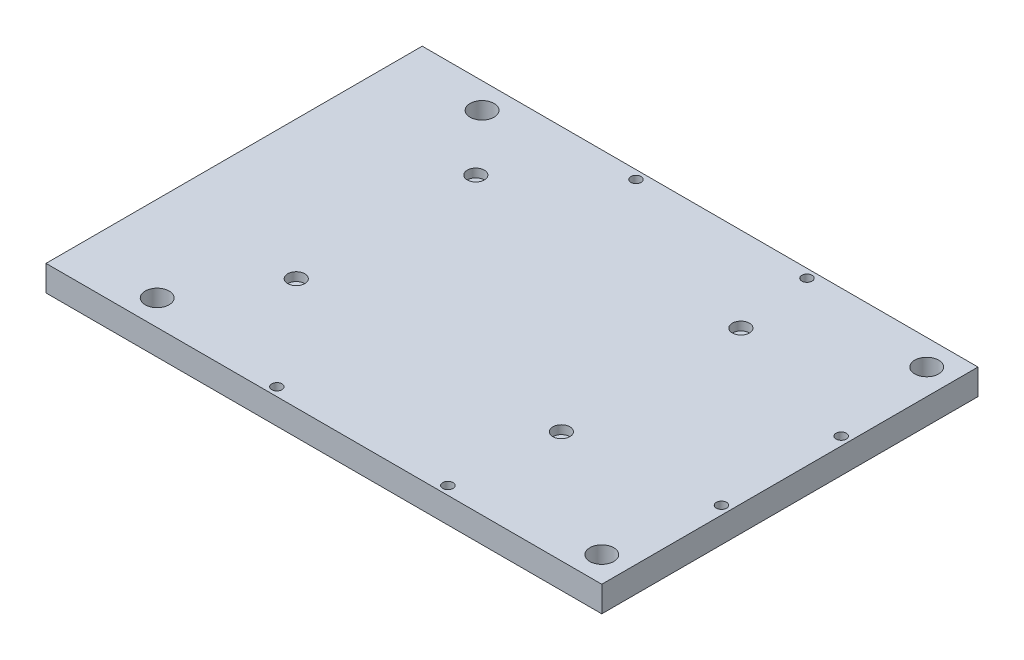
SolidWorks part; units mm, degrees
ref_plane "Front Plane" through (0, 0, 0) normal (0, 0, 1) x (1, 0, 0)
ref_plane "Top Plane" through (0, 0, 0) normal (0, 1, 0) x (1, 0, 0)
ref_plane "Right Plane" through (0, 0, 0) normal (1, 0, 0) x (0, 0, -1)
sketch "Sketch2" plane through (0, 0, 0) normal (0, 1, 0) x (1, 0, 0)
  line L0 (-154.9031, -110) -> (170.0969, -110)
  line L7 (-154.9031, 110) -> (-154.9031, -110)
  line L22 (170.0969, -110) -> (170.0969, 110)
  line L24 (70.8088, -52.5) -> (63.3088, -52.5)
  line L25 (70.8088, -60) -> (70.8088, -52.5)
  line L26 (170.0969, 0) -> (170.0969, 35)
  line L27 (70.8088, 60) -> (50.8088, 60)
  line L28 (-154.9031, 110) -> (170.0969, 110)
  line L29 (170.0969, 35) -> (165.0969, 35)
  line L30 (70.8088, -60) -> (70.8088, 60)
  line L31 (-99.1912, -60) -> (-99.1912, 0)
  line L32 (50.8088, -60) -> (-99.1912, -60)
  line L33 (-99.1912, 60) -> (50.8088, 60)
  line L34 (-99.1912, 0) -> (-99.1912, 60)
  line L35 (50.8088, -60) -> (70.8088, -60)
  circle A11 centre (155.0969, -95) radius 7
  circle A13 centre (155.0969, 95) radius 7
  circle A14 centre (-104.9031, -95) radius 7
  circle A20 centre (-104.9031, 95) radius 7
  circle A21 centre (-24.9031, 105) radius 3
  circle A22 centre (75.0969, 105) radius 3
  circle A23 centre (75.0969, -105) radius 3
  circle A24 centre (-24.9031, -105) radius 3
  circle A25 centre (165.0969, 35) radius 3
  circle A26 centre (165.0969, -35) radius 3
  circle A31 centre (63.3088, 52.5) radius 5
  circle A32 centre (-91.6912, 52.5) radius 5
  circle A33 centre (-91.6912, -52.5) radius 5
  circle A34 centre (63.3088, -52.5) radius 5
  point P4 (0, 0)
extrude "Boss-Extrude3" add sketch "Sketch2" against normal blind 15 contours A22 | A11 | L7 L0 L22 L28 | A14 | A20 | A21 | A13 | A25 | A26 | A23 | A24
sketch "Sketch4" plane through (0, 0, 0) normal (0, 1, 0) x (1, 0, 0)
  circle A27 centre (-73.9629, -44.5929) radius 5
  circle A28 centre (81.0371, -44.5929) radius 5
  circle A29 centre (81.0371, 60.4071) radius 5
  circle A30 centre (-73.9629, 60.4071) radius 5
  point P14 (-25.8479, 7.9071)
  dimension "D1" = 2
  dimension "D2" = 2
sketch "Sketch11" plane through (0, -15, 0) normal (0, -1, 0) x (1, 0, 0)
  line L74 (155.0969, -80) -> (155.0969, -5)
  line L75 (155.0969, 5) -> (155.0969, 80)
  line L77 (135.0969, 95) -> (135.0969, 80)
  line L78 (135.0969, 80) -> (155.0969, 80)
  line L79 (155.0969, -80) -> (135.0969, -80)
  line L80 (135.0969, -80) -> (135.0969, -95)
  line L82 (85.0969, -95) -> (85.0969, -5)
  line L83 (85.0969, 95) -> (85.0969, 5)
  line L84 (85.0969, -5) -> (155.0969, -5)
  line L85 (85.0969, 5) -> (155.0969, 5)
  line L86 (85.0969, 95) -> (135.0969, 95)
  line L87 (-134.9031, -80) -> (-84.9031, -80)
  line L88 (-134.9031, -80) -> (-134.9031, -5)
  line L89 (-134.9031, -5) -> (-84.9031, -5)
  line L90 (-84.9031, -80) -> (-84.9031, -5)
  line L91 (-134.9031, 5) -> (-84.9031, 5)
  line L92 (-134.9031, 5) -> (-134.9031, 80)
  line L93 (-134.9031, 80) -> (-84.9031, 80)
  line L94 (-84.9031, 5) -> (-84.9031, 80)
  line L95 (-74.9031, -95) -> (-4.9031, -95)
  line L96 (-74.9031, -95) -> (-74.9031, -5)
  line L97 (-74.9031, -5) -> (-4.9031, -5)
  line L98 (-4.9031, -95) -> (-4.9031, -5)
  line L99 (5.0969, -95) -> (75.0969, -95)
  line L100 (5.0969, -95) -> (5.0969, -5)
  line L101 (5.0969, -5) -> (75.0969, -5)
  line L102 (75.0969, -95) -> (75.0969, -5)
  line L103 (-74.9031, 5) -> (-4.9031, 5)
  line L104 (-74.9031, 5) -> (-74.9031, 95)
  line L105 (-74.9031, 95) -> (-4.9031, 95)
  line L106 (-4.9031, 5) -> (-4.9031, 95)
  line L107 (5.0969, 5) -> (75.0969, 5)
  line L108 (5.0969, 5) -> (5.0969, 95)
  line L109 (5.0969, 95) -> (75.0969, 95)
  line L110 (75.0969, 5) -> (75.0969, 95)
  line L111 (85.0969, -95) -> (135.0969, -95)
extrude "Cut-Extrude2" cut sketch "Sketch11" against normal blind 8 contours L103 L106 L105 L104 | L107 L110 L109 L108 | L86 L83 L85 L75 L78 L77 | L82 L111 L80 L79 L74 L84 | L99 L102 L101 L100 | L95 L98 L97 L96 | L87 L90 L89 L88 | L94 L93 L92 L91
fillet "Fillet1" radius 3 35 edges at (85.0969, -11, 5) (5.0969, -11, 5) (-74.9031, -11, 5) (85.0969, -11, -95) (5.0969, -11, -95) (-74.9031, -11, -95) (-134.9031, -11, -80) (-134.9031, -11, 5) (-84.9031, -11, -5) (-84.9031, -11, 80) (-4.9031, -11, 95) (75.0969, -11, 95) (75.0969, -11, -5) (155.0969, -11, -5) (155.0969, -11, 80) (135.0969, -11, 95) (135.0969, -11, 80) (135.0969, -11, -80) (155.0969, -11, -80) (135.0969, -11, -95) (75.0969, -11, -95) (-4.9031, -11, -95) (-84.9031, -11, -80) (-84.9031, -11, 5) (-4.9031, -11, 5) (75.0969, -11, 5) (155.0969, -11, 5) (5.0969, -11, -5) (85.0969, -11, -5) (85.0969, -11, 95) (5.0969, -11, 95) (-74.9031, -11, 95) (-74.9031, -11, -5) (-134.9031, -11, -5) (-134.9031, -11, 80)
extrude "Cut-Extrude3" cut sketch "Sketch4" against normal blind 5 contours A27 | A30 | A29 | A28
sketch "Sketch12" plane through (-154.9031, 0, 0) normal (-1, 0, 0) x (0, 0, 1)
  line L0 (-110, -7.5) -> (-102.5, -7.5)
  line L1 (-110, -15) -> (-110, 0) construction
  circle A0 centre (-102.5, -7.5) radius 3
  circle A1 centre (-34.33, -7.5) radius 3
  circle A2 centre (33.84, -7.5) radius 3
  circle A3 centre (102.01, -7.5) radius 3
  dimension "D1" = 4
extrude "Cut-Extrude4" cut sketch "Sketch12" against normal blind 5 contours A0 | A1 | A2 | A3
